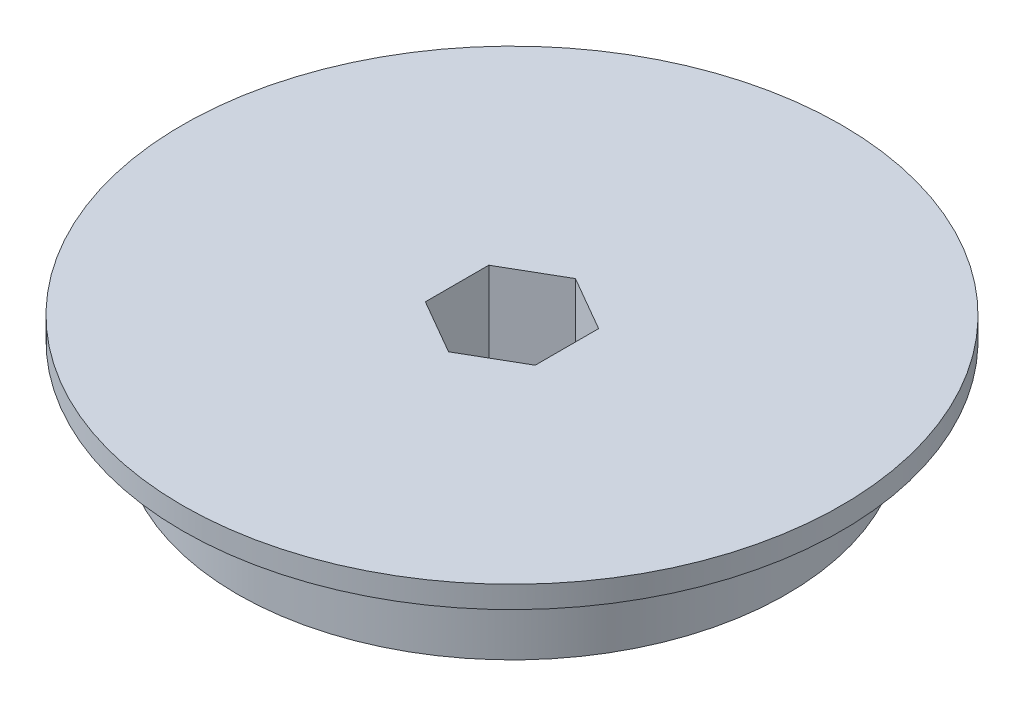
SolidWorks part; units mm, degrees
ref_plane "Спереди" through (0, 0, 0) normal (0, 0, 1) x (1, 0, 0)
ref_plane "Сверху" through (0, 0, 0) normal (0, 1, 0) x (1, 0, 0)
ref_plane "Справа" through (0, 0, 0) normal (1, 0, 0) x (0, 0, -1)
sketch "Sketch1" plane through (0, 0, 0) normal (0, 1, 0) x (1, 0, 0)
  line L1 (0, 2.3094) -> (-2, 1.1547)
  line L2 (-2, 1.1547) -> (-2, -1.1547)
  line L3 (-2, -1.1547) -> (0, -2.3094)
  line L4 (0, -2.3094) -> (2, -1.1547)
  line L5 (2, -1.1547) -> (2, 1.1547)
  line L6 (2, 1.1547) -> (0, 2.3094)
  circle A0 centre (0, 0) radius 10
  circle A1 centre (0, 0) radius 2 construction
  dimension "D1" = 20
extrude "Boss-Extrude1" add sketch "Sketch1" along normal blind 3
sketch "Sketch3" plane through (0, 3, 0) normal (0, 1, 0) x (1, 0, 0)
  circle A0 centre (0, 0) radius 12
extrude "Boss-Extrude2" add sketch "Sketch3" along normal blind 0.8
sketch "Sketch4" plane through (0, 0, 0) normal (0, -1, 0) x (1, 0, 0)
  line L6 (0, -2.3094) -> (2, -1.1547)
  line L7 (-2, -1.1547) -> (0, -2.3094)
  line L8 (-2, 1.1547) -> (-2, -1.1547)
  line L9 (0, 2.3094) -> (-2, 1.1547)
  line L10 (2, 1.1547) -> (0, 2.3094)
  line L11 (2, -1.1547) -> (2, 1.1547)
  line L12 (0, -2.3094) -> (2, -1.1547)
  line L13 (-2, -1.1547) -> (0, -2.3094)
  line L14 (-2, 1.1547) -> (-2, -1.1547)
  line L15 (0, 2.3094) -> (-2, 1.1547)
  line L16 (2, 1.1547) -> (0, 2.3094)
  line L17 (2, -1.1547) -> (2, 1.1547)
  dimension "D1" = 0
extrude "Cut-Extrude1" cut sketch "Sketch4" against normal through all
chamfer "Chamfer1" distance 0.4 angle 45 1 edges at (0, 3, 10)
